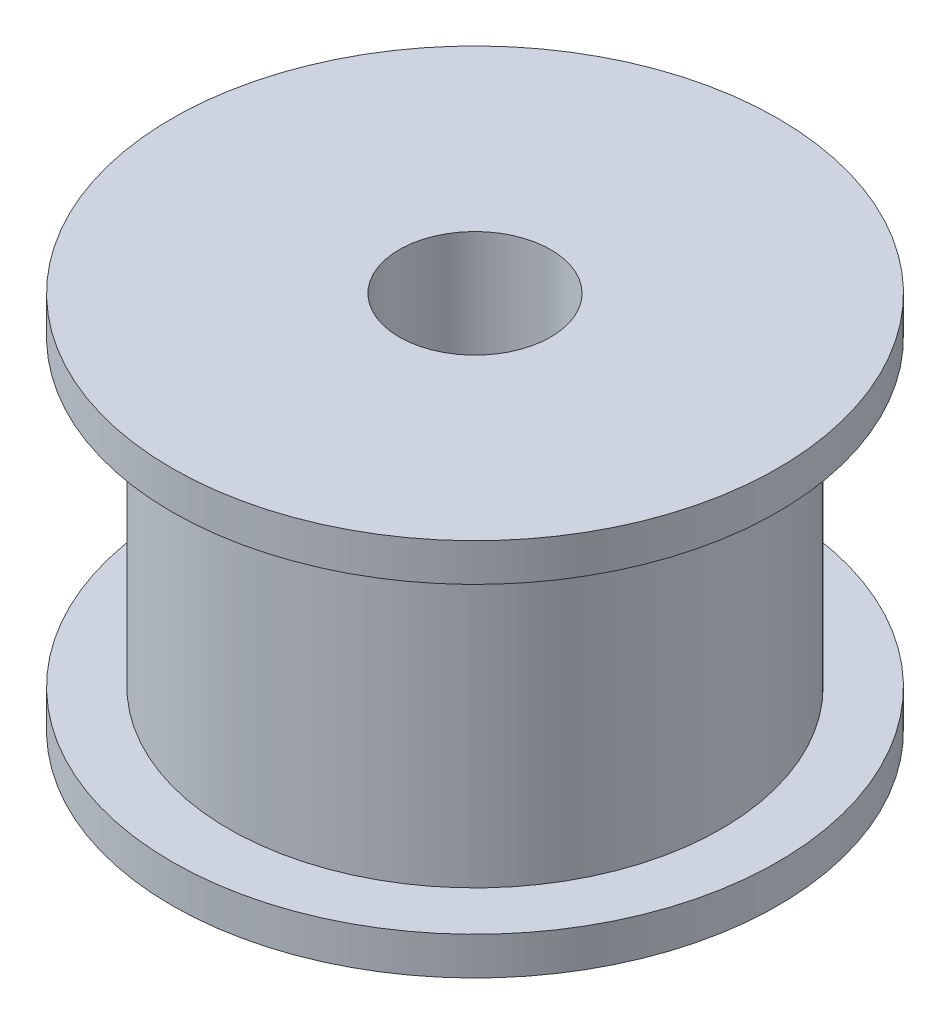
SolidWorks part; units mm, degrees
ref_plane "Front Plane" through (0, 0, 0) normal (0, 0, 1) x (1, 0, 0)
ref_plane "Top Plane" through (0, 0, 0) normal (0, 1, 0) x (1, 0, 0)
ref_plane "Right Plane" through (0, 0, 0) normal (1, 0, 0) x (0, 0, -1)
sketch "Sketch2" plane through (0, 0, 0) normal (0, 0, 1) x (1, 0, 0)
  line L1 (0, 0) -> (-8, 0)
  line L2 (0, 0) -> (0, -1)
  line L3 (0, -1) -> (-8, -1)
  line L4 (-8, 0) -> (-8, -1)
  line L5 (0, 0) -> (-6.5, 0)
  line L6 (0, 0) -> (0, 8)
  line L7 (0, 8) -> (-6.5, 8)
  line L8 (-6.5, 0) -> (-6.5, 8)
  line L9 (0, 8) -> (-8, 8)
  line L10 (0, 8) -> (0, 9)
  line L11 (0, 9) -> (-8, 9)
  line L12 (-8, 8) -> (-8, 9)
  dimension "D1" = 1
  dimension "D2" = 8
  dimension "D3" = 6.5
  dimension "D4" = 8
  dimension "D5" = 1
  dimension "D6" = 10
revolve "Revolve1" add sketch "Sketch2" angle 360 about L6
sketch "Sketch4" plane through (0, 9, 0) normal (0, 1, 0) x (1, 0, 0)
  circle A0 centre (0, 0) radius 2
  dimension "D1" = 4
extrude "Cut-Extrude1" cut sketch "Sketch4" against normal blind 10
